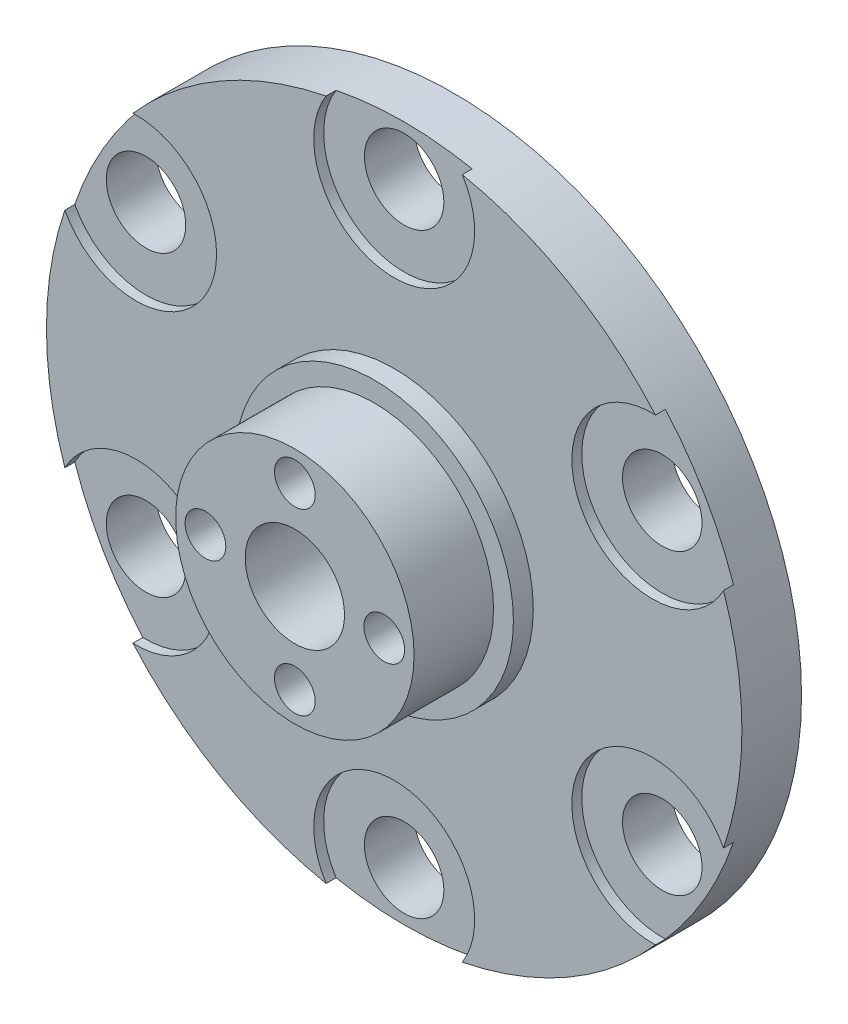
SolidWorks part; units mm, degrees
material "6061 合金"
ref_plane "前视基准面" through (0, 0, 0) normal (0, 0, 1) x (1, 0, 0)
ref_plane "上视基准面" through (0, 0, 0) normal (0, 1, 0) x (1, 0, 0)
ref_plane "右视基准面" through (0, 0, 0) normal (1, 0, 0) x (0, 0, -1)
other "Configuration Table"
sketch "草图1" plane through (0, 0, 0) normal (0, 0, 1) x (1, 0, 0)
  circle A1 centre (0, 0) radius 2.5
  circle A10 centre (0, 0) radius 15 construction
  circle A14 centre (0, 15) radius 2
  circle A16 centre (0, 0) radius 17.5
  circle A17 centre (12.9904, 7.5) radius 2
  circle A18 centre (12.9904, -7.5) radius 2
  circle A19 centre (0, -15) radius 2
  circle A20 centre (-12.9904, -7.5) radius 2
  circle A21 centre (-12.9904, 7.5) radius 2
  point P19 (-0.4246, -0.4242)
  point P20 (0, 0)
  dimension "D1" = 5
  dimension "D2" = 30
  dimension "D3" = 4
  dimension "D4" = 35
  dimension "D5" = 6
extrude "凸台-拉伸1" add sketch "草图1" along normal blind 3
sketch "草图2" plane through (0, 0, 3) normal (0, 0, 1) x (1, 0, 0)
  circle A0 centre (0, 0) radius 6
  circle A1 centre (0, 0) radius 2.5
  dimension "D1" = 12
  dimension "D2" = 5
extrude "凸台-拉伸2" add sketch "草图2" along normal blind 5
sketch "草图3" plane through (0, 0, 0) normal (0, 0, -1) x (-1, 0, 0)
  circle A0 centre (0, 0) radius 3
  circle A1 centre (0, 0) radius 12
  dimension "D1" = 24
  dimension "D2" = 6
extrude "凸台-拉伸3" [suppressed] add sketch "草图3" along normal blind 2
sketch "草图4" plane through (0, 0, 3) normal (0, 0, 1) x (1, 0, 0)
  circle A0 centre (12.9904, 7.5) radius 4.05
  circle A1 centre (12.9904, -7.5) radius 4.05
  circle A2 centre (0, -15) radius 4.05
  circle A3 centre (-12.9904, -7.5) radius 4.05
  circle A4 centre (-12.9904, 7.5) radius 4.05
  circle A5 centre (0, 15) radius 4.05
  point P15 (0, 0)
  dimension "D1" = 8.1
  dimension "D2" = 6
extrude "切除-拉伸2" cut sketch "草图4" against normal blind 0.5
sketch "草图5" plane through (0, 0, 8) normal (0, 0, 1) x (1, 0, 0)
  circle A0 centre (0, 0) radius 4.5 construction
  circle A1 centre (0, 4.5) radius 1.025
  circle A2 centre (4.5, 0) radius 1.025
  circle A3 centre (0, -4.5) radius 1.025
  circle A4 centre (-4.5, 0) radius 1.025
  point P14 (0, 0)
  dimension "D1" = 9
  dimension "D2" = 2.05
  dimension "D3" = 4
extrude "切除-拉伸3" cut sketch "草图5" against normal blind 5
sketch "草图6" plane through (0, 0, 3) normal (0, 0, 1) x (1, 0, 0)
  circle A0 centre (0, 0) radius 7
  circle A1 centre (0, 0) radius 5.9797
  dimension "D1" = 14
extrude "凸台-拉伸4" add sketch "草图6" along normal blind 1
